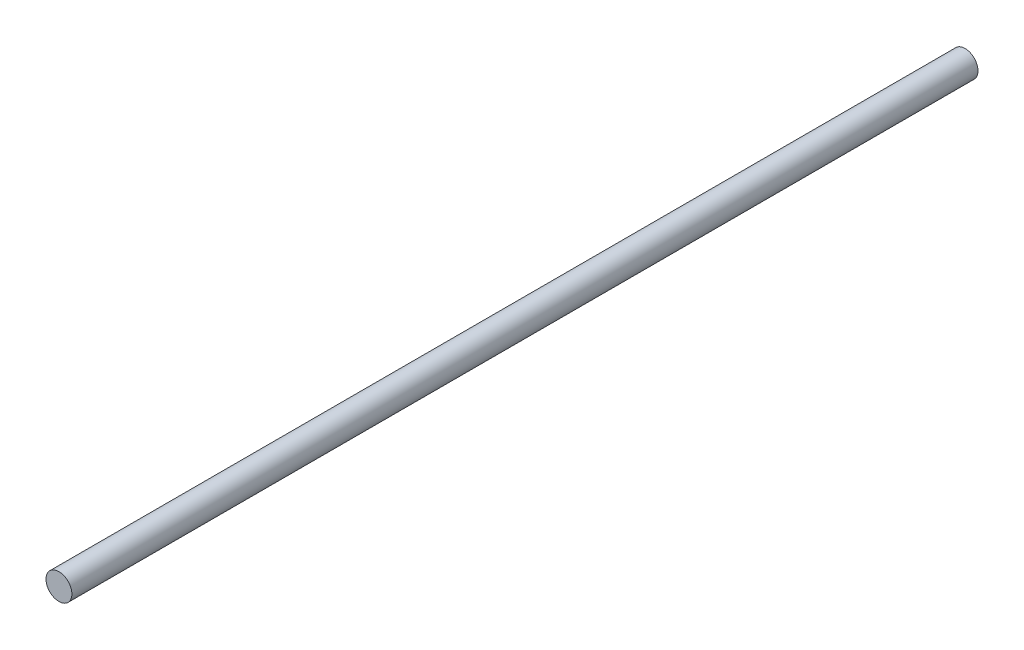
SolidWorks part; units mm, degrees
material "Balsa"
ref_plane "Front Plane" through (0, 0, 0) normal (0, 0, 1) x (1, 0, 0)
ref_plane "Top Plane" through (0, 0, 0) normal (0, 1, 0) x (1, 0, 0)
ref_plane "Right Plane" through (0, 0, 0) normal (1, 0, 0) x (0, 0, -1)
sketch "Sketch1" plane through (0, 0, 0) normal (0, 0, 1) x (1, 0, 0)
  circle A0 centre (0, 0) radius 2
  dimension "D1" = 4
extrude "Boss-Extrude1" add sketch "Sketch1" along normal blind 140
